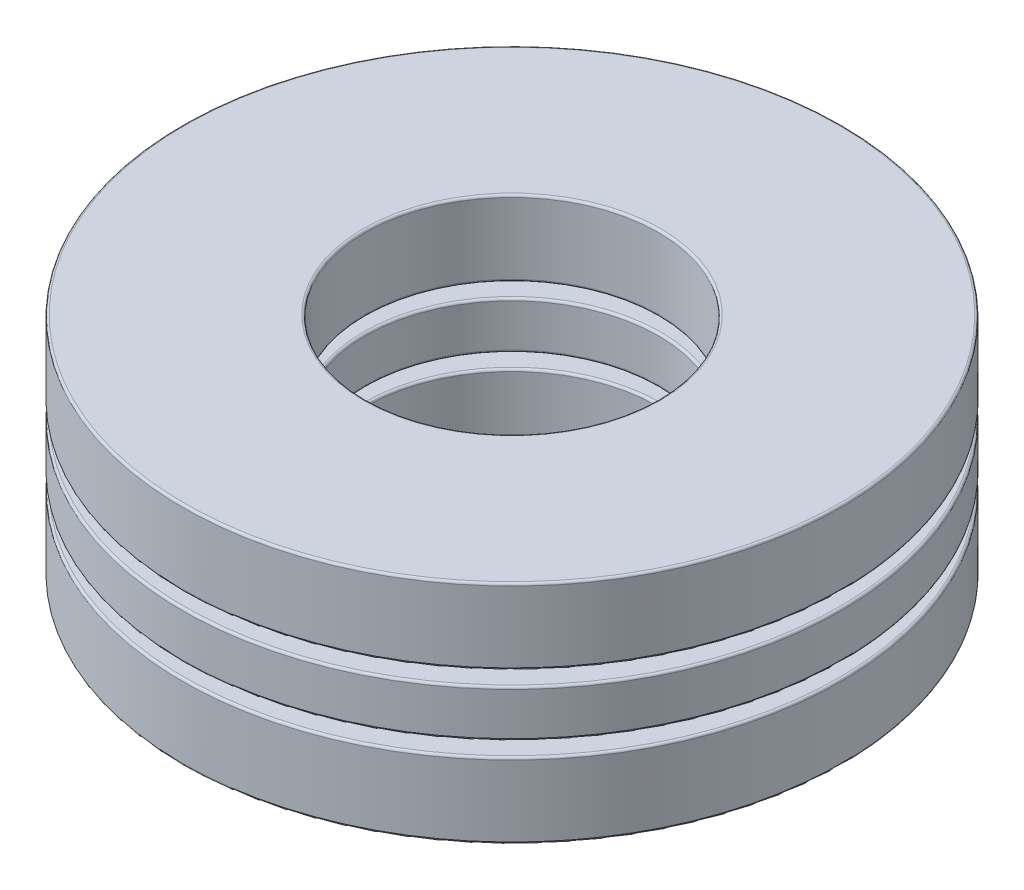
SolidWorks part; units mm, degrees
ref_plane "Front Plane" through (0, 0, 0) normal (0, 0, 1) x (1, 0, 0)
ref_plane "Top Plane" through (0, 0, 0) normal (0, 1, 0) x (1, 0, 0)
ref_plane "Right Plane" through (0, 0, 0) normal (1, 0, 0) x (0, 0, -1)
sketch "Sketch1" plane through (0, 0, 0) normal (1, 0, 0) x (0, 0, -1)
  line L0 (-7.1438, 0) -> (7.1438, 0) construction
  line L1 (0, -2.4511) -> (0, 2.4511) construction
  line L2 (-7.1438, 0.5106) -> (-3.175, 0.5106)
  line L3 (-7.1438, 0.5106) -> (-7.1438, -0.5106)
  line L4 (-7.1438, -0.5106) -> (-3.175, -0.5106)
  line L5 (-3.175, 0.5106) -> (-3.175, -0.5106)
  line L6 (-5.1594, 0.817) -> (-5.1594, -0.817) construction
  circle A0 centre (-5.1594, 0) radius 0.817 construction
  point P13 (-5.1594, 0.5106)
  dimension "D1" = 1.6341
  dimension "OD" = 14.2875
  dimension "Shaft Dia" = 6.35
  dimension "Th" = 4.9022
  dimension "D2" = 1.0213
revolve "Revolve1" add sketch "Sketch1" angle 360 about L1
sketch "Sketch3" plane through (0, 0, 0) normal (1, 0, 0) x (0, 0, -1)
  line L0 (-5.1594, 0.817) -> (-5.1594, -0.817)
  arc A0 (-5.1594, 0.817) -> (-5.1594, -0.817) centre (-5.1594, 0) ccw
  circle A1 centre (-5.1594, 0) radius 0.817 construction
revolve "Cut-Revolve1" cut sketch "Sketch3" angle 360 about L0
sketch "Sketch2" plane through (0, 0, 0) normal (1, 0, 0) x (0, 0, -1)
  line L0 (-5.1594, 0.817) -> (-5.1594, -0.817)
  arc A0 (-5.1594, 0.817) -> (-5.1594, -0.817) centre (-5.1594, 0) ccw
  circle A2 centre (-5.1594, 0) radius 0.817 construction
revolve "Revolve2" add sketch "Sketch2" angle 360 about L0
ref_axis "Axis1" through (0, 2.4511, 0) along (0, -1, 0)
pattern_circular "CirPattern1" count 7 every 51.429 about axis through (0, 2.4511, 0) along (0, -1, 0) of bodies 187
pattern_circular "CirPattern2" count 7 every 51.429 about axis through (0, 0, 0) along (0, 1, 0) of "Cut-Revolve1"
sketch "Sketch4" plane through (0, 0, 0) normal (1, 0, 0) x (0, 0, -1)
  line L0 (-7.1438, 0.5106) -> (-7.1438, -0.5106) construction
  line L1 (-7.1438, 0.817) -> (-3.175, 0.817)
  line L2 (-7.1438, 0.817) -> (-7.1438, 2.4511)
  line L3 (-7.1438, 2.4511) -> (-3.175, 2.4511)
  line L4 (-3.175, 0.817) -> (-3.175, 2.4511)
  line L5 (-7.1438, -2.4511) -> (-3.175, -2.4511)
  line L6 (-7.1438, -2.4511) -> (-7.1438, -0.817)
  line L7 (-7.1438, -0.817) -> (-3.175, -0.817)
  line L8 (-3.175, -2.4511) -> (-3.175, -0.817)
  line L9 (-5.1594, 0.817) -> (-5.1594, -0.817) construction
  line L10 (-3.175, 0.5106) -> (-3.175, -0.5106) construction
  line L11 (0, 0) -> (-7.1438, 0) construction
  line L12 (-7.1438, 0) -> (7.1438, 0) construction
  dimension "Ht" = 4.9022
revolve "Revolve3" add sketch "Sketch4" angle 360 about L1
fillet "Fillet1" radius 0.049 4 edges at (0, 0.817, -3.175) (0, 2.4511, -3.175) (0, 0.817, -7.1438) (0, 2.4511, -7.1438)
fillet "Fillet2" radius 0.049 4 edges at (0, -0.5106, -3.175) (0, 0.5106, -3.175) (0, -0.5106, -7.1438) (0, 0.5106, -7.1438)
fillet "Fillet3" radius 0.049 4 edges at (0, -2.4511, -3.175) (0, -0.817, -3.175) (0, -2.4511, -7.1438) (0, -0.817, -7.1438)
equation "\"D1@Sketch1\" = \"Th@Sketch1\"/3"
equation "\"D2@Sketch1\" = \"D1@Sketch1\"*.625"
equation "\"Balls@CirPattern1\" = \"OD@Sketch1\"*12"
equation "\"Angle@CirPattern1\" = 360/\"Balls@CirPattern1\""
equation "\"D1@CirPattern2\" = \"Balls@CirPattern1\""
equation "\"D2@CirPattern2\" = \"Angle@CirPattern1\""
equation "\"D1@Fillet1\" = \"Th@Sketch1\"*.01"
equation "\"D1@Fillet2\" = \"D1@Fillet1\""
equation "\"D1@Fillet3\" = \"D1@Fillet1\""
